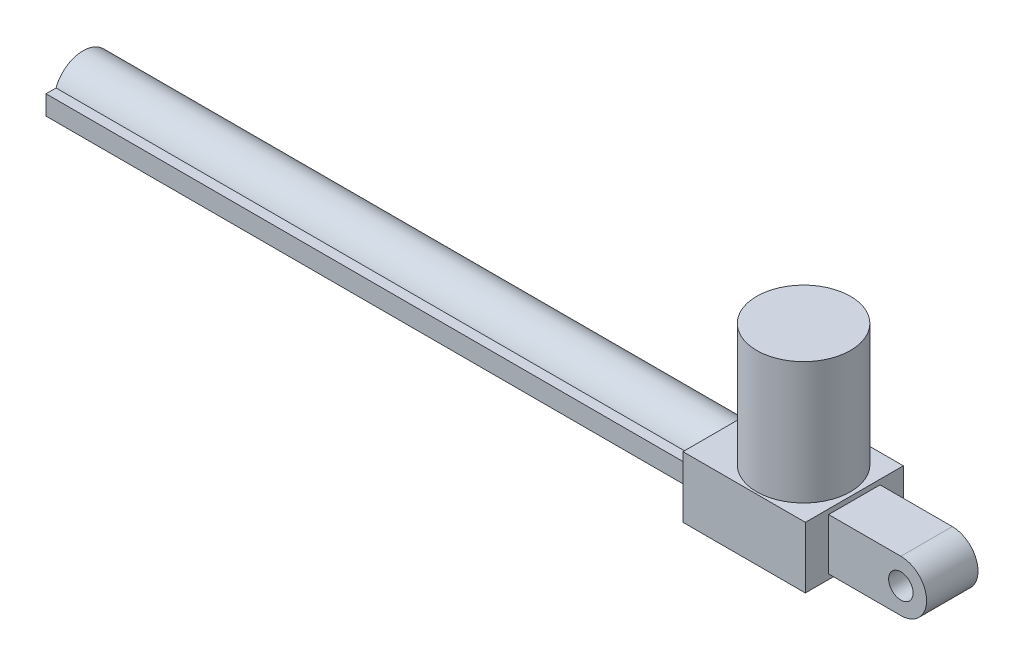
SolidWorks part; units mm, degrees
ref_plane "Front Plane" through (0, 0, 0) normal (0, 0, 1) x (1, 0, 0)
ref_plane "Top Plane" through (0, 0, 0) normal (0, 1, 0) x (1, 0, 0)
ref_plane "Right Plane" through (0, 0, 0) normal (1, 0, 0) x (0, 0, -1)
sketch "Sketch1" plane through (0, 0, 0) normal (0, 1, 0) x (1, 0, 0)
  line L1 (-114.0351, 23.6842) -> (-64.0351, 23.6842)
  line L2 (-114.0351, 23.6842) -> (-114.0351, -16.3158)
  line L3 (-114.0351, -16.3158) -> (-64.0351, -16.3158)
  line L4 (-64.0351, 23.6842) -> (-64.0351, -16.3158)
  dimension "D1" = 50
  dimension "D2" = 40
extrude "Boss-Extrude1" add sketch "Sketch1" along normal blind 25
sketch "Sketch2" plane through (0, 25, 0) normal (0, 1, 0) x (1, 0, 0)
  line L0 (-84.7705, 23.6842) -> (-84.7705, -16.3158)
  line L1 (-64.0351, 23.6842) -> (-114.0351, 23.6842) construction
  line L2 (-114.0351, -16.3158) -> (-64.0351, -16.3158) construction
  circle A0 centre (-84.7705, 3.6842) radius 19.1586
extrude "Boss-Extrude2" add sketch "Sketch2" along normal blind 50 contours L0 A0 | L0 A0
sketch "Sketch3" plane through (-114.0351, 0, 0) normal (-1, 0, 0) x (0, 0, 1)
  line L0 (-3.6842, 25) -> (-3.6842, 0)
  line L1 (-23.6842, 25) -> (16.3158, 25) construction
  line L2 (-23.6842, 0) -> (16.3158, 0) construction
  line L4 (5.8301, 16.6432) -> (11.4453, 16.6432)
  line L5 (5.8301, 16.6432) -> (5.8301, 8.7356)
  line L6 (5.8301, 8.7356) -> (11.4453, 8.7356)
  line L7 (11.4453, 16.6432) -> (11.4453, 8.7356)
  circle A0 centre (-3.6842, 12.5) radius 11.7864
  circle A1 centre (-3.6842, 12.5) radius 9.5143
  dimension "D1" = 19.0285
extrude "Boss-Extrude3" add sketch "Sketch3" along normal blind 265 contours A1 L0 A0 | A1 L5 L4 A0 L0 | L6 A0 L4 L5 | A1 L0 A0 L6 L5 | A0 L6 L7 L4
sketch "Sketch4" plane through (-64.0351, 0, 0) normal (1, 0, 0) x (0, 0, -1)
  line L0 (-16.3158, 25) -> (23.6842, 25)
  line L1 (23.6842, 25) -> (3.6842, 25)
  line L2 (3.6842, 25) -> (3.6842, 0)
  line L3 (-16.3158, 0) -> (23.6842, 0) construction
  line L5 (-6.8158, 23) -> (14.1842, 23)
  line L6 (-6.8158, 23) -> (-6.8158, 2)
  line L7 (-6.8158, 2) -> (14.1842, 2)
  line L8 (14.1842, 23) -> (14.1842, 2)
  dimension "D1" = 10.5
  dimension "D2" = 10.5
  dimension "D3" = 2
  dimension "D4" = 2
extrude "Boss-Extrude4" add sketch "Sketch4" along normal blind 40 contours L6 L7 L2 L5 | L8 L5 L2 L7
sketch "Sketch5" plane through (0, 0, 6.8158) normal (0, 0, 1) x (1, 0, 0)
  line L1 (-24.0351, 23) -> (-64.0351, 23) construction
  line L2 (-24.0351, 23) -> (-24.0351, 2) construction
  line L4 (-34.5351, 23) -> (-34.5423, 23)
  line L6 (-34.5423, 2) -> (-34.5351, 2)
  circle A0 centre (-34.5351, 12.5) radius 10.5
  circle A1 centre (-34.5351, 12.5) radius 5
  arc A2 (-34.5351, 23) -> (-34.5351, 2) centre (-34.5351, 12.5) cw
  arc A3 (-34.5423, 23) -> (-34.5351, 2) centre (-34.5351, 12.5) cw
  point P6 (-24.0351, 12.5)
  line M2 (-64.0351, 2) -> (-24.0351, 2)
  line M3 (-24.0351, 2) -> (-24.0351, 23)
  line M4 (-24.0351, 23) -> (-64.0351, 23)
  dimension "D1" = 21
  dimension "D3" = 10.5
  dimension "D2" = 10.5
extrude "Cut-Extrude3" cut sketch "Sketch5" against normal blind 25 and the other way through all contours A0 M3 M4 | A0 M2 M3 | A1
